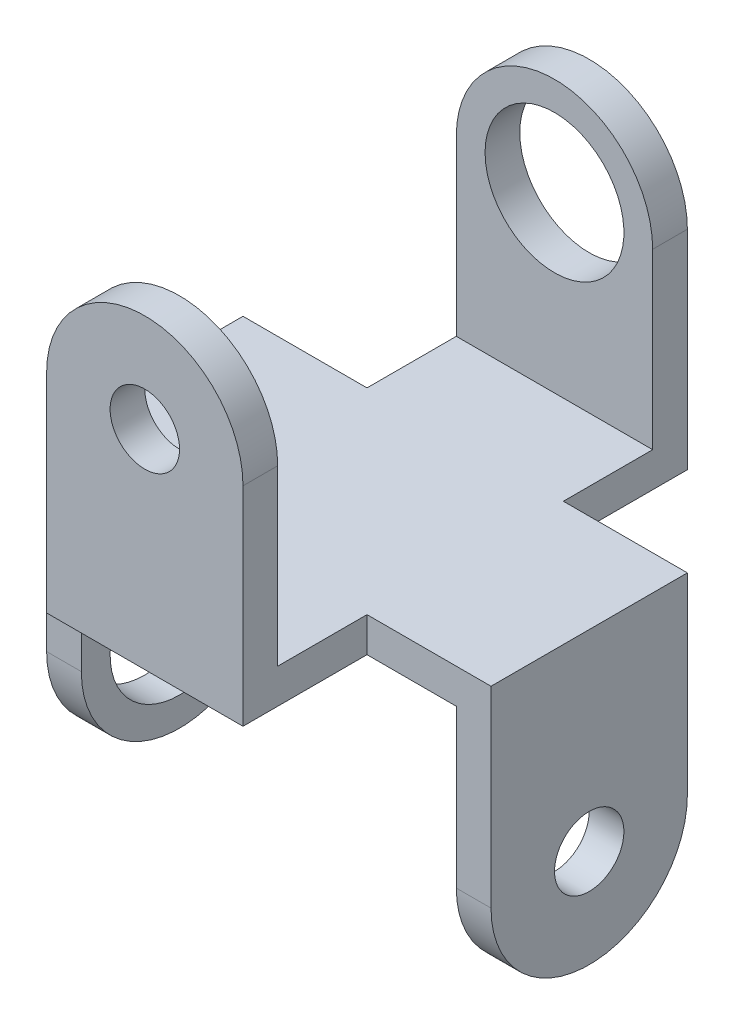
SolidWorks part; units mm, degrees
ref_plane "Front Plane" through (0, 0, 0) normal (0, 0, 1) x (1, 0, 0)
ref_plane "Top Plane" through (0, 0, 0) normal (0, 1, 0) x (1, 0, 0)
ref_plane "Right Plane" through (0, 0, 0) normal (1, 0, 0) x (0, 0, -1)
sketch "Model" plane through (0, 0, 0) normal (0, 0, 1) x (1, 0, 0)
  line L0 (13.8616, 4.1327) -> (42.1458, 4.1327)
  line L1 (13.8616, 4.1327) -> (13.8616, 29.1327)
  line L2 (42.1458, 29.1327) -> (42.1458, 4.1327)
  arc A0 (42.1458, 29.1327) -> (13.8616, 29.1327) centre (28.0037, 29.1327) ccw
extrude "Boss-Extrude1" add sketch "Model" along normal blind 5
sketch "Sketch2" plane through (0, 0, 5) normal (0, 0, 1) x (1, 0, 0)
  circle A0 centre (28.0037, 29.1327) radius 2.05
  dimension "D1" = 4.1
extrude "Cut-Extrude1" cut sketch "Sketch2" against normal blind 5
sketch "Sketch3" plane through (0, 4.1327, 0) normal (0, -1, 0) x (1, 0, 0)
  line L1 (13.8616, 5) -> (42.1458, 5)
  line L2 (13.8616, 5) -> (13.8616, 0)
  line L3 (13.8616, 0) -> (42.1458, 0)
  line L4 (42.1458, 5) -> (42.1458, 0)
extrude "Boss-Extrude3" add sketch "Sketch3" along normal blind 5
sketch "Sketch4" plane through (0, 0, 5) normal (0, 0, 1) x (1, 0, 0)
  line L0 (42.1458, -0.8673) -> (42.1458, 29.1327) construction
  line L1 (13.8616, -0.8673) -> (42.1458, -0.8673)
  line L2 (13.8616, -0.8673) -> (13.8616, 4.1327)
  line L3 (13.8616, 4.1327) -> (42.1458, 4.1327)
  line L4 (42.1458, -0.8673) -> (42.1458, 4.1327)
extrude "Boss-Extrude4" add sketch "Sketch4" along normal blind 54.01
sketch "Sketch5" plane through (0, 0, 59.01) normal (0, 0, 1) x (1, 0, 0)
  line L0 (42.1458, -0.8673) -> (42.1458, 4.1327) construction
  line L1 (13.8616, -0.8673) -> (42.1458, -0.8673) construction
  line L2 (13.8616, 4.1327) -> (13.8616, -0.8673) construction
  line L3 (13.8616, 4.1327) -> (42.1458, 4.1327)
  line L4 (42.1458, 4.1327) -> (42.1458, 29.1327)
  line L5 (13.8616, 29.1327) -> (13.8616, 4.1327)
  line L7 (42.1458, 4.1327) -> (42.1458, 29.1327)
  line L8 (13.8616, 29.1327) -> (13.8616, 4.1327)
  line L9 (42.1458, -0.8673) -> (42.1458, 4.1327)
  line L10 (13.8616, -0.8673) -> (42.1458, -0.8673)
  line L11 (13.8616, 4.1327) -> (13.8616, -0.8673)
  arc A1 (42.1458, 29.1327) -> (13.8616, 29.1327) centre (28.0037, 29.1327) ccw
  arc A2 (42.1458, 29.1327) -> (13.8616, 29.1327) centre (28.0037, 29.1327) ccw
  dimension "D1" = 0
extrude "Boss-Extrude5" add sketch "Sketch5" along normal blind 5
sketch "Sketch6" plane through (0, -0.8673, 0) normal (0, -1, 0) x (1, 0, 0)
  line L0 (0.9987, 32.005) -> (55.0087, 32.005) construction
  line L1 (0.9987, 46.1471) -> (55.0087, 46.1471)
  line L2 (0.9987, 17.8628) -> (55.0087, 17.8628)
  line L3 (28.0037, 32.005) -> (28.0037, 64.01)
  line L4 (13.8616, 64.01) -> (42.1458, 64.01) construction
  line L5 (0.9987, 46.1471) -> (0.9987, 17.8628)
  line L6 (55.0087, 46.1471) -> (55.0087, 17.8628)
  line M2 (13.8616, 64.01) -> (13.8616, 0)
  line M4 (42.1458, 0) -> (42.1458, 64.01)
  dimension "D2" = 14.1421
  dimension "D1" = 14.1422
  dimension "D3" = 14.1422
extrude "Boss-Extrude7" add sketch "Sketch6" against normal blind 5 contours L0 L3 L1 M2 | L0 L6 L1 M4 | L3 L0 L1 M4 | L5 L0 L1 M2 | L0 L5 L2 M2 | L0 L2 M2 M4 | L0 L2 L6 M4
sketch "Sketch8" plane through (0.9987, 0, 0) normal (-1, 0, 0) x (0, 0, 1)
  line L1 (17.8628, 4.1327) -> (46.1471, 4.1327)
  line L2 (17.8628, 4.1327) -> (17.8628, -0.8673)
  line L3 (17.8628, -0.8673) -> (46.1471, -0.8673)
  line L4 (46.1471, 4.1327) -> (46.1471, -0.8673)
extrude "Boss-Extrude8" add sketch "Sketch8" along normal blind 5
sketch "Sketch10" plane through (0, -0.8673, 0) normal (0, -1, 0) x (1, 0, 0)
  line L0 (-4.0013, 17.8628) -> (13.8616, 17.8628) construction
  line L1 (-4.0013, 46.1471) -> (0.9987, 46.1471)
  line L2 (-4.0013, 46.1471) -> (-4.0013, 17.8628)
  line L3 (-4.0013, 17.8628) -> (0.9987, 17.8628)
  line L4 (0.9987, 46.1471) -> (0.9987, 17.8628)
  dimension "D1" = 5
extrude "Boss-Extrude9" add sketch "Sketch10" along normal blind 22.6808
sketch "Sketch11" plane through (-4.0013, 0, 0) normal (-1, 0, 0) x (0, 0, 1)
  line L0 (46.1471, -23.5481) -> (17.8628, -23.5481) construction
  line L1 (46.1471, -23.5481) -> (17.8628, -23.5481)
  arc A0 (17.8628, -23.5481) -> (46.1471, -23.5481) centre (32.005, -23.5481) ccw
extrude "Boss-Extrude10" add sketch "Sketch11" against normal blind 5
sketch "Sketch12" plane through (55.0087, 0, 0) normal (1, 0, 0) x (0, 0, -1)
  line L4 (-46.1471, -0.8673) -> (-17.8628, -0.8673)
  line L5 (-17.8628, -0.8673) -> (-17.8628, 4.1327)
  line L6 (-17.8628, 4.1327) -> (-46.1471, 4.1327)
  line L7 (-46.1471, 4.1327) -> (-46.1471, -0.8673)
  line L8 (-46.1471, -0.8673) -> (-17.8628, -0.8673)
  line L9 (-17.8628, -0.8673) -> (-17.8628, 4.1327)
  line L10 (-17.8628, 4.1327) -> (-46.1471, 4.1327)
  line L11 (-46.1471, 4.1327) -> (-46.1471, -0.8673)
  dimension "D1" = 0
extrude "Boss-Extrude11" add sketch "Sketch12" along normal blind 5
sketch "Sketch14" plane through (60.0087, 0, 0) normal (1, 0, 0) x (0, 0, -1)
  line L3 (-17.8628, -0.8673) -> (-46.1471, -0.8673)
  line L4 (-46.1471, -0.8673) -> (-46.1471, -23.5481)
  line L5 (-17.8628, -23.5481) -> (-17.8628, -0.8673)
  line L6 (-17.8628, -0.8673) -> (-46.1471, -0.8673)
  line L7 (-46.1471, -0.8673) -> (-46.1471, -23.5481)
  line L8 (-17.8628, -23.5481) -> (-17.8628, -0.8673)
  arc A1 (-46.1471, -23.5481) -> (-17.8628, -23.5481) centre (-32.005, -23.5481) ccw
  arc A2 (-46.1471, -23.5481) -> (-17.8628, -23.5481) centre (-32.005, -23.5481) ccw
  dimension "D1" = 0
extrude "Boss-Extrude12" add sketch "Sketch14" against normal blind 5
sketch "Sketch15" plane through (0, 0, 64.01) normal (0, 0, 1) x (1, 0, 0)
  circle A0 centre (28.0037, 29.1327) radius 5
  dimension "D1" = 10
extrude "Cut-Extrude3" cut sketch "Sketch15" against normal blind 5
sketch "Sketch16" plane through (60.0087, 0, 0) normal (1, 0, 0) x (0, 0, -1)
  circle A0 centre (-32.005, -23.5481) radius 5
  dimension "D1" = 10
extrude "Cut-Extrude4" cut sketch "Sketch16" against normal blind 14.1
sketch "Sketch17" plane through (-4.0013, 0, 0) normal (-1, 0, 0) x (0, 0, 1)
  circle A0 centre (32.005, -23.5481) radius 2.05
  dimension "D1" = 4.1
extrude "Cut-Extrude5" cut sketch "Sketch17" against normal blind 8.1
sketch "Sketch18" plane through (0, 0, 0) normal (0, 0, -1) x (-1, 0, 0)
  circle A0 centre (-28.0037, 29.1327) radius 10
  dimension "D1" = 20
extrude "Cut-Extrude6" cut sketch "Sketch18" against normal blind 5
sketch "Sketch19" plane through (-4.0013, 0, 0) normal (-1, 0, 0) x (0, 0, 1)
  circle A0 centre (32.005, -23.5481) radius 10
  dimension "D1" = 20
extrude "Cut-Extrude7" cut sketch "Sketch19" against normal blind 5
